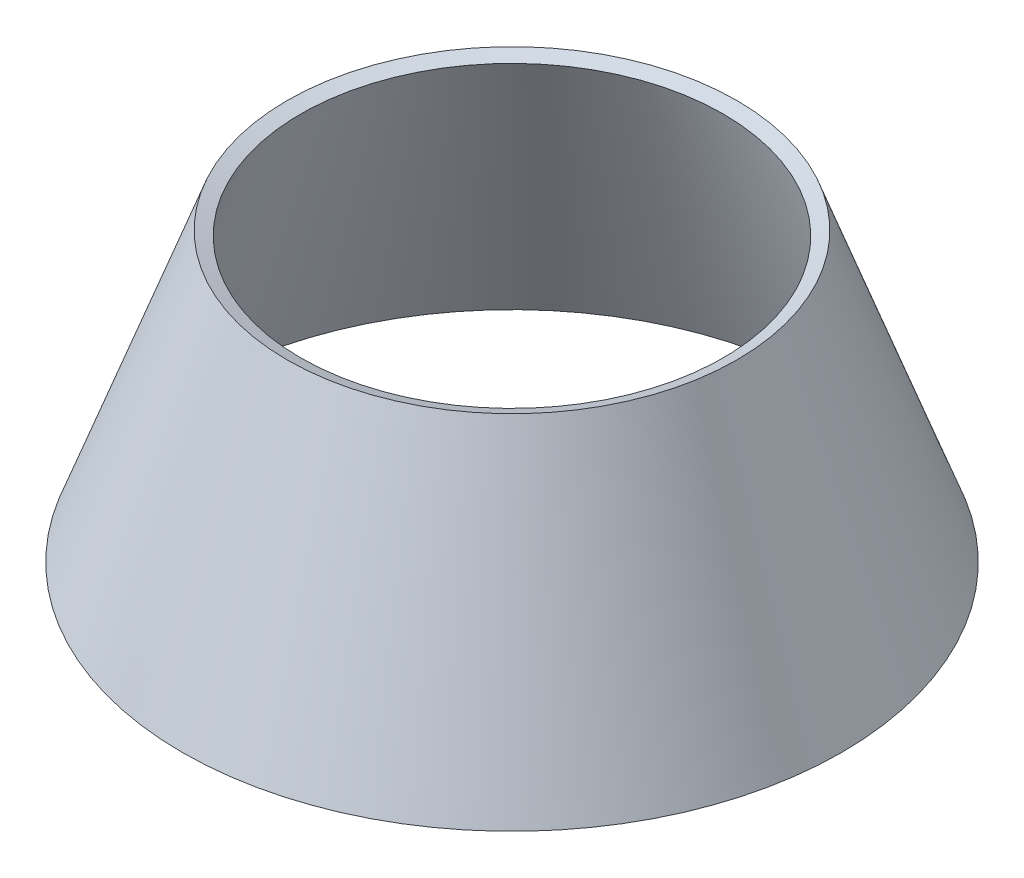
SolidWorks part; units mm, degrees
ref_plane "Front Plane" through (0, 0, 0) normal (0, 0, 1) x (1, 0, 0)
ref_plane "Top Plane" through (0, 0, 0) normal (0, 1, 0) x (1, 0, 0)
ref_plane "Right Plane" through (0, 0, 0) normal (1, 0, 0) x (0, 0, -1)
sketch "Sketch2" plane through (0, 0, 0) normal (0, 0, 1) x (1, 0, 0)
  line L0 (0, 0) -> (0, 30) construction
  line L1 (0, 30) -> (22.05, 30) construction
  line L2 (22.05, 30) -> (33, 0) construction
  line L3 (33, 0) -> (0, 0) construction
  line L4 (33, 0) -> (56.9153, 0) construction
  line L9 (33, 0) -> (22.05, 30)
  dimension "D1" = 22.05
  dimension "D2" = 33
  dimension "D3" = 30
revolve "Revolve-Thin1" add sketch "Sketch2" angle 360 about L0
